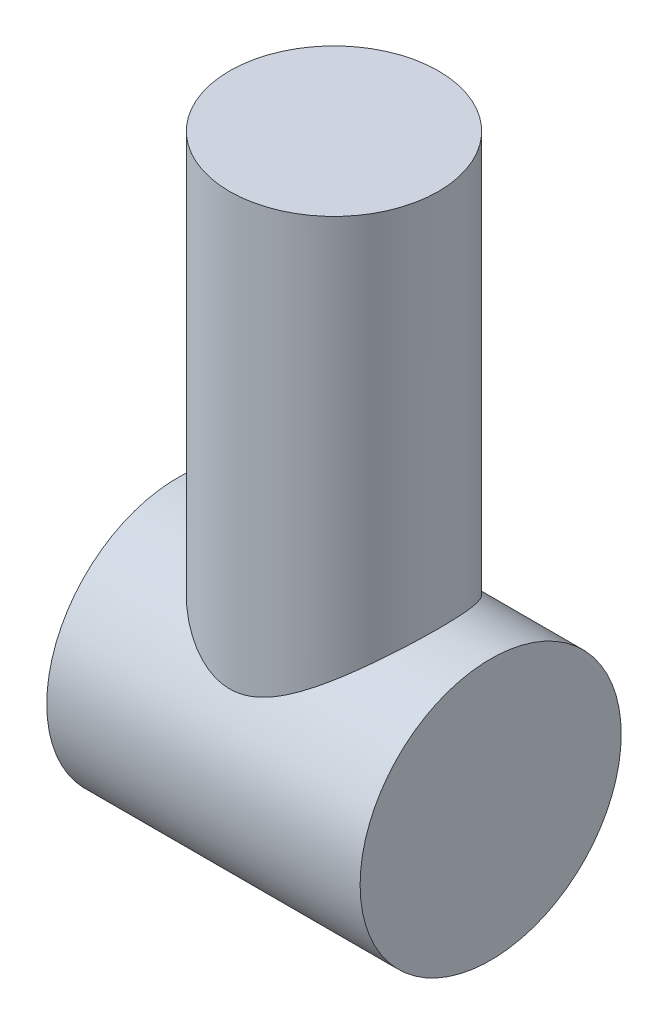
SolidWorks part; units mm, degrees
ref_plane "前视基准面" through (0, 0, 0) normal (0, 0, 1) x (1, 0, 0)
ref_plane "上视基准面" through (0, 0, 0) normal (0, 1, 0) x (1, 0, 0)
ref_plane "右视基准面" through (0, 0, 0) normal (1, 0, 0) x (0, 0, -1)
sketch "草图2" plane through (0, 0, 0) normal (1, 0, 0) x (0, 0, -1)
  circle A0 centre (0, 0) radius 50
  dimension "D1" = 100
extrude "凸台-拉伸1" add sketch "草图2" along normal mid plane 120
sketch "草图3" plane through (0, 0, 0) normal (0, 1, 0) x (1, 0, 0)
  circle A0 centre (0, 0) radius 40
  dimension "D1" = 80
extrude "凸台-拉伸2" add sketch "草图3" along normal blind 195
